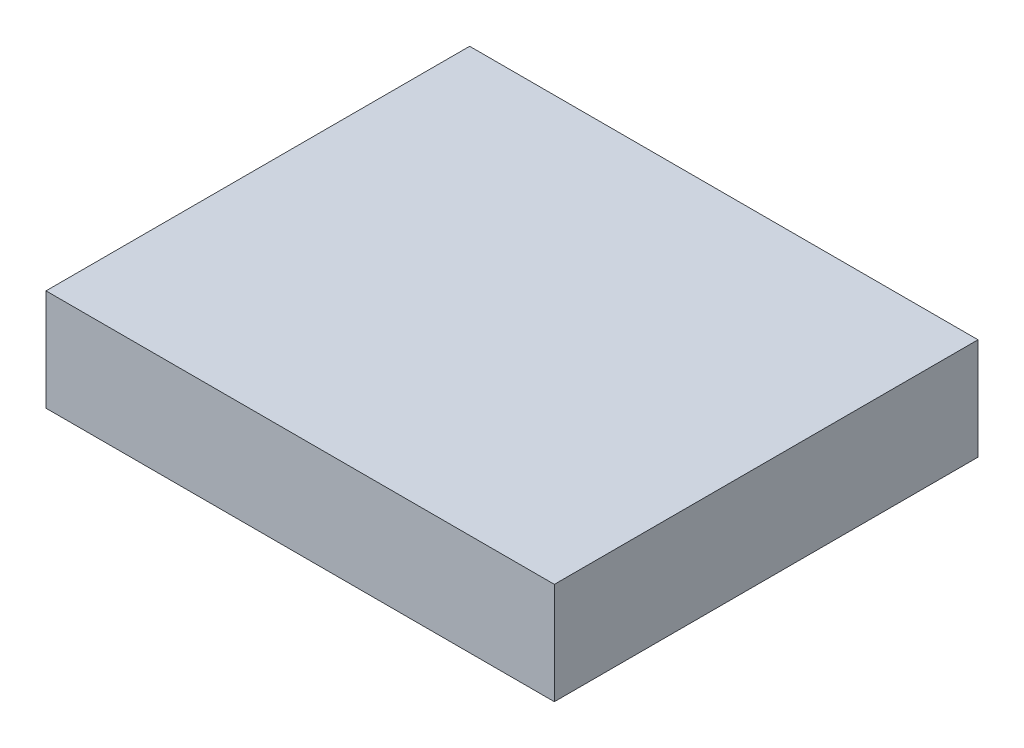
SolidWorks part; units mm, degrees
ref_plane "Front Plane" through (0, 0, 0) normal (0, 0, 1) x (1, 0, 0)
ref_plane "Top Plane" through (0, 0, 0) normal (0, 1, 0) x (1, 0, 0)
ref_plane "Right Plane" through (0, 0, 0) normal (1, 0, 0) x (0, 0, -1)
other "Configuration Table"
sketch "Sketch1" plane through (0, 0, 0) normal (0, 0, 1) x (1, 0, 0)
  line L1 (320, 1254) -> (380, 1254)
  line L2 (320, 1254) -> (320, 1266)
  line L3 (320, 1266) -> (380, 1266)
  line L4 (380, 1254) -> (380, 1266)
extrude "PRESS_uc_catal_flans_ISO9409_1" add sketch "Sketch1" against normal blind 50 from offset 550 separate body
